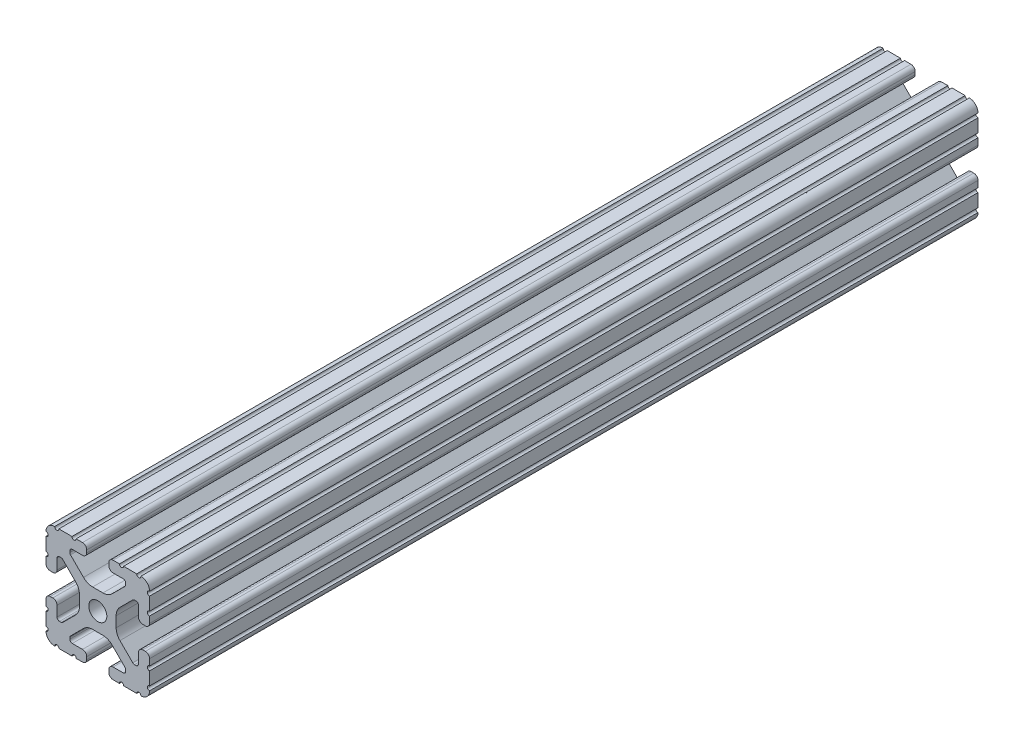
SolidWorks part; units mm, degrees
material "AISI 1020"
ref_plane "Front Plane" through (0, 0, 0) normal (0, 0, 1) x (1, 0, 0)
ref_plane "Top Plane" through (0, 0, 0) normal (0, 1, 0) x (1, 0, 0)
ref_plane "Right Plane" through (0, 0, 0) normal (1, 0, 0) x (0, 0, -1)
ref_plane "Plane1" through (0, 0, -304.8) normal (0, 0, -1) x (-1, 0, 0)
sketch "Sketch1" plane through (0, 0, -304.8) normal (0, 0, -1) x (-1, 0, 0)
  line L0 (14.3277, 19.05) -> (9.4982, 19.05)
  line L1 (7.9742, 19.05) -> (5.6176, 19.05)
  line L2 (4.064, 17.4964) -> (4.064, 16.5396)
  line L3 (5.6176, 14.986) -> (9.3853, 14.986)
  line L4 (10.287, 14.0843) -> (10.287, 13.5524)
  line L5 (10.0229, 12.9148) -> (5.2522, 8.144)
  line L6 (1.9022, 6.7564) -> (-1.9022, 6.7564)
  line L7 (-5.2522, 8.144) -> (-10.0229, 12.9148)
  line L8 (-10.287, 13.5524) -> (-10.287, 14.0843)
  line L9 (-9.3853, 14.986) -> (-5.6176, 14.986)
  line L10 (-4.064, 16.5396) -> (-4.064, 17.4964)
  line L11 (-5.6176, 19.05) -> (-7.9742, 19.05)
  line L12 (-9.4982, 19.05) -> (-14.3277, 19.05)
  line L13 (-19.05, 14.3277) -> (-19.05, 9.4961)
  line L14 (-19.05, 7.9763) -> (-19.05, 5.6176)
  line L15 (-17.4964, 4.064) -> (-16.5396, 4.064)
  line L16 (-14.986, 5.6176) -> (-14.986, 9.3853)
  line L17 (-14.0843, 10.287) -> (-13.516, 10.287)
  line L18 (-12.8784, 10.0229) -> (-8.1476, 5.2921)
  line L19 (-6.7564, 1.9335) -> (-6.7564, -1.9335)
  line L20 (-8.1476, -5.2921) -> (-12.8784, -10.0229)
  line L21 (-13.516, -10.287) -> (-14.0843, -10.287)
  line L22 (-14.986, -9.3853) -> (-14.986, -5.6176)
  line L23 (-16.5396, -4.064) -> (-17.4964, -4.064)
  line L24 (-19.05, -5.6176) -> (-19.05, -7.9763)
  line L25 (-19.05, -9.4961) -> (-19.05, -14.3277)
  line L26 (-14.3277, -19.05) -> (-9.4961, -19.05)
  line L27 (-7.9763, -19.05) -> (-5.6176, -19.05)
  line L28 (-4.064, -17.4964) -> (-4.064, -16.5396)
  line L29 (-5.6176, -14.986) -> (-9.3853, -14.986)
  line L30 (-10.287, -14.0843) -> (-10.287, -13.5524)
  line L31 (-10.0229, -12.9148) -> (-5.2522, -8.144)
  line L32 (-1.9022, -6.7564) -> (1.9022, -6.7564)
  line L33 (5.2522, -8.144) -> (10.0229, -12.9148)
  line L34 (10.287, -13.5524) -> (10.287, -14.0843)
  line L35 (9.3853, -14.986) -> (5.6176, -14.986)
  line L36 (4.064, -16.5396) -> (4.064, -17.4964)
  line L37 (5.6176, -19.05) -> (7.9763, -19.05)
  line L38 (9.4961, -19.05) -> (14.3277, -19.05)
  line L39 (19.05, -14.3277) -> (19.05, -9.4961)
  line L40 (19.05, -7.9763) -> (19.05, -5.6176)
  line L41 (17.4964, -4.064) -> (16.5396, -4.064)
  line L42 (14.986, -5.6176) -> (14.986, -9.3853)
  line L43 (14.0843, -10.287) -> (13.516, -10.287)
  line L44 (12.8784, -10.0229) -> (8.1476, -5.2921)
  line L45 (6.7564, -1.9335) -> (6.7564, 1.9335)
  line L46 (8.1476, 5.2921) -> (12.8784, 10.0229)
  line L47 (13.516, 10.287) -> (14.0843, 10.287)
  line L48 (14.986, 9.3853) -> (14.986, 5.6176)
  line L49 (16.5396, 4.064) -> (17.4964, 4.064)
  line L50 (19.05, 5.6176) -> (19.05, 7.9763)
  line L51 (19.05, 9.4961) -> (19.05, 14.3277)
  line L52 (19.05, 5.6176) -> (17.4964, 5.6176) construction
  line L53 (17.4964, 5.6176) -> (17.4964, 4.064) construction
  line L54 (17.4964, 5.6176) -> (18.5393, 4.466) construction
  arc A0 (15.8475, 19.05) -> (14.3277, 19.05) centre (15.0876, 18.9933) cw
  arc A1 (9.4982, 19.05) -> (7.9742, 19.05) centre (8.7362, 19.05) cw
  arc A2 (5.6176, 19.05) -> (4.064, 17.4964) centre (5.6176, 17.4964) ccw
  arc A3 (4.064, 16.5396) -> (5.6176, 14.986) centre (5.6176, 16.5396) ccw
  arc A4 (9.3853, 14.986) -> (10.287, 14.0843) centre (9.3853, 14.0843) cw
  arc A5 (10.287, 13.5524) -> (10.0229, 12.9148) centre (9.3853, 13.5524) cw
  arc A6 (5.2522, 8.144) -> (1.9022, 6.7564) centre (1.9022, 11.494) cw
  arc A7 (-1.9022, 6.7564) -> (-5.2522, 8.144) centre (-1.9022, 11.494) cw
  arc A8 (-10.0229, 12.9148) -> (-10.287, 13.5524) centre (-9.3853, 13.5524) cw
  arc A9 (-10.287, 14.0843) -> (-9.3853, 14.986) centre (-9.3853, 14.0843) cw
  arc A10 (-5.6176, 14.986) -> (-4.064, 16.5396) centre (-5.6176, 16.5396) ccw
  arc A11 (-4.064, 17.4964) -> (-5.6176, 19.05) centre (-5.6176, 17.4964) ccw
  arc A12 (-7.9742, 19.05) -> (-9.4982, 19.05) centre (-8.7362, 19.05) cw
  arc A13 (-14.3277, 19.05) -> (-15.8475, 19.05) centre (-15.0876, 18.9933) cw
  arc A14 (-15.8475, 19.05) -> (-19.05, 15.8475) centre (-15.8751, 15.8751) ccw
  arc A15 (-19.05, 15.8475) -> (-19.05, 14.3277) centre (-18.9933, 15.0876) cw
  arc A16 (-19.05, 9.4961) -> (-19.05, 7.9763) centre (-18.9933, 8.7362) cw
  arc A17 (-19.05, 5.6176) -> (-17.4964, 4.064) centre (-17.4964, 5.6176) ccw
  arc A18 (-16.5396, 4.064) -> (-14.986, 5.6176) centre (-16.5396, 5.6176) ccw
  arc A19 (-14.986, 9.3853) -> (-14.0843, 10.287) centre (-14.0843, 9.3853) cw
  arc A20 (-13.516, 10.287) -> (-12.8784, 10.0229) centre (-13.516, 9.3853) cw
  arc A21 (-8.1476, 5.2921) -> (-6.7564, 1.9335) centre (-11.5062, 1.9335) cw
  arc A22 (-6.7564, -1.9335) -> (-8.1476, -5.2921) centre (-11.5062, -1.9335) cw
  arc A23 (-12.8784, -10.0229) -> (-13.516, -10.287) centre (-13.516, -9.3853) cw
  arc A24 (-14.0843, -10.287) -> (-14.986, -9.3853) centre (-14.0843, -9.3853) cw
  arc A25 (-14.986, -5.6176) -> (-16.5396, -4.064) centre (-16.5396, -5.6176) ccw
  arc A26 (-17.4964, -4.064) -> (-19.05, -5.6176) centre (-17.4964, -5.6176) ccw
  arc A27 (-19.05, -7.9763) -> (-19.05, -9.4961) centre (-18.9933, -8.7362) cw
  arc A28 (-19.05, -14.3277) -> (-19.05, -15.8475) centre (-18.9933, -15.0876) cw
  arc A29 (-19.05, -15.8475) -> (-15.8475, -19.05) centre (-15.8751, -15.8751) ccw
  arc A30 (-15.8475, -19.05) -> (-14.3277, -19.05) centre (-15.0876, -18.9933) cw
  arc A31 (-9.4961, -19.05) -> (-7.9763, -19.05) centre (-8.7362, -18.9933) cw
  arc A32 (-5.6176, -19.05) -> (-4.064, -17.4964) centre (-5.6176, -17.4964) ccw
  arc A33 (-4.064, -16.5396) -> (-5.6176, -14.986) centre (-5.6176, -16.5396) ccw
  arc A34 (-9.3853, -14.986) -> (-10.287, -14.0843) centre (-9.3853, -14.0843) cw
  arc A35 (-10.287, -13.5524) -> (-10.0229, -12.9148) centre (-9.3853, -13.5524) cw
  arc A36 (-5.2522, -8.144) -> (-1.9022, -6.7564) centre (-1.9022, -11.494) cw
  arc A37 (1.9022, -6.7564) -> (5.2522, -8.144) centre (1.9022, -11.494) cw
  arc A38 (10.0229, -12.9148) -> (10.287, -13.5524) centre (9.3853, -13.5524) cw
  arc A39 (10.287, -14.0843) -> (9.3853, -14.986) centre (9.3853, -14.0843) cw
  arc A40 (5.6176, -14.986) -> (4.064, -16.5396) centre (5.6176, -16.5396) ccw
  arc A41 (4.064, -17.4964) -> (5.6176, -19.05) centre (5.6176, -17.4964) ccw
  arc A42 (7.9763, -19.05) -> (9.4961, -19.05) centre (8.7362, -18.9933) cw
  arc A43 (14.3277, -19.05) -> (15.8475, -19.05) centre (15.0876, -18.9933) cw
  arc A44 (15.8475, -19.05) -> (19.05, -15.8475) centre (15.8751, -15.8751) ccw
  arc A45 (19.05, -15.8475) -> (19.05, -14.3277) centre (18.9933, -15.0876) cw
  arc A46 (19.05, -9.4961) -> (19.05, -7.9763) centre (18.9933, -8.7362) cw
  arc A47 (19.05, -5.6176) -> (17.4964, -4.064) centre (17.4964, -5.6176) ccw
  arc A48 (16.5396, -4.064) -> (14.986, -5.6176) centre (16.5396, -5.6176) ccw
  arc A49 (14.986, -9.3853) -> (14.0843, -10.287) centre (14.0843, -9.3853) cw
  arc A50 (13.516, -10.287) -> (12.8784, -10.0229) centre (13.516, -9.3853) cw
  arc A51 (8.1476, -5.2921) -> (6.7564, -1.9335) centre (11.5062, -1.9335) cw
  arc A52 (6.7564, 1.9335) -> (8.1476, 5.2921) centre (11.5062, 1.9335) cw
  arc A53 (12.8784, 10.0229) -> (13.516, 10.287) centre (13.516, 9.3853) cw
  arc A54 (14.0843, 10.287) -> (14.986, 9.3853) centre (14.0843, 9.3853) cw
  arc A55 (14.986, 5.6176) -> (16.5396, 4.064) centre (16.5396, 5.6176) ccw
  arc A56 (17.4964, 4.064) -> (19.05, 5.6176) centre (17.4964, 5.6176) ccw
  arc A57 (19.05, 7.9763) -> (19.05, 9.4961) centre (18.9933, 8.7362) cw
  arc A58 (19.05, 14.3277) -> (19.05, 15.8475) centre (18.9933, 15.0876) cw
  arc A59 (19.05, 15.8475) -> (15.8475, 19.05) centre (15.8751, 15.8751) ccw
  circle A60 centre (0, 0) radius 3.3274
sketch "Sketch2" plane through (0, 0, 0) normal (0, 1, 0) x (1, 0, 0)
  line L1 (0, 0) -> (0, 304.8)
sweep "Sweep4" add profiles "Sketch1" path "Sketch2"
